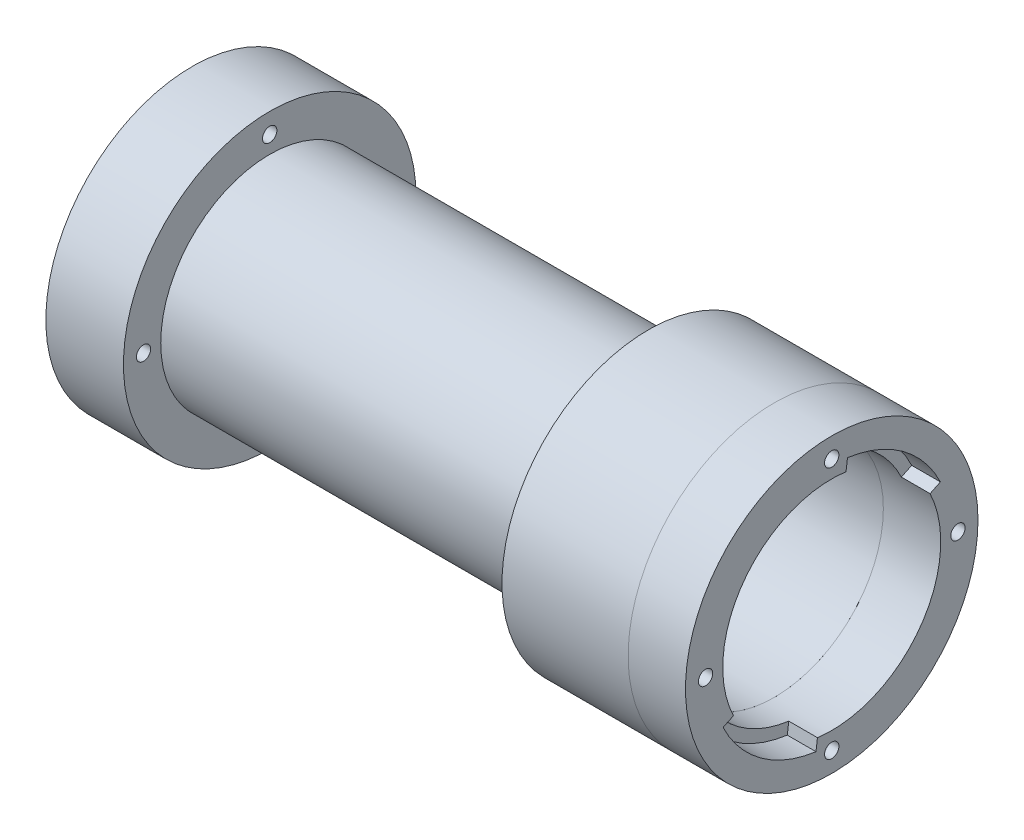
SolidWorks part; units mm, degrees
ref_plane "前视基准面" through (0, 0, 0) normal (0, 0, 1) x (1, 0, 0)
ref_plane "上视基准面" through (0, 0, 0) normal (0, 1, 0) x (1, 0, 0)
ref_plane "右视基准面" through (0, 0, 0) normal (1, 0, 0) x (0, 0, -1)
sketch "草图1" plane through (0, 0, 0) normal (1, 0, 0) x (0, 0, -1)
  circle A0 centre (0, 0) radius 31
  circle A1 centre (0, 0) radius 51
extrude "凸台-拉伸1" add sketch "草图1" along normal blind 18 and the other way blind 9.06
sketch "草图2" plane through (18, 0, 0) normal (1, 0, 0) x (0, 0, -1)
  circle A0 centre (0, 0) radius 27
  circle A1 centre (0, 0) radius 38
extrude "凸台-拉伸2" add sketch "草图2" along normal blind 132
sketch "草图3" plane through (150, 0, 0) normal (1, 0, 0) x (0, 0, -1)
  circle A0 centre (0, 0) radius 38
  circle A1 centre (0, 0) radius 51
extrude "凸台-拉伸3" add sketch "草图3" along normal blind 63.98 separate body
sketch "草图4" plane through (-9.06, 0, 0) normal (-1, 0, 0) x (0, 0, 1)
  line L0 (0, 0) -> (60.5842, 0) construction
  line L1 (60.5842, 0) -> (-61.6406, 0) construction
  line L2 (0, 0) -> (0, 71.2022) construction
  line L3 (0, 71.2022) -> (0, -60.4245) construction
  circle A0 centre (0, 44) radius 2.5
  circle A1 centre (44, 0) radius 2.5
  circle A2 centre (0, -44) radius 2.5
  circle A3 centre (-44, 0) radius 2.5
  point P17 (0, 0)
  dimension "D1" = 4
extrude "切除-拉伸1" cut sketch "草图4" against normal up to surface (223.04 mm away)
sketch "草图5" plane through (213.98, 0, 0) normal (1, 0, 0) x (0, 0, -1)
  line L12 (4.9791, 37.6724) -> (5.5032, 41.6379)
  line L13 (34.278, 16.4018) -> (37.8862, 18.1283)
  line L14 (-4.9791, -37.6724) -> (-5.5032, -41.6379)
  line L15 (-34.278, -16.4018) -> (-37.8862, -18.1283)
  arc A2 (34.278, 16.4018) -> (29.8966, 23.4563) centre (0, 0) ccw
  circle A3 centre (0, 0) radius 38 construction
  arc A5 (-34.278, -16.4018) -> (-29.8966, -23.4563) centre (0, 0) ccw
  arc A6 (16.9401, 34.0152) -> (29.8966, 23.4563) centre (0, 0) cw
  arc A10 (18.7233, 37.5957) -> (33.0436, 25.9253) centre (0, 0) cw
  arc A15 (18.7233, 37.5957) -> (5.5032, 41.6379) centre (0, 0) ccw
  arc A16 (33.0436, 25.9253) -> (37.8862, 18.1283) centre (0, 0) cw
  arc A17 (16.9401, 34.0152) -> (4.9791, 37.6724) centre (0, 0) ccw
  arc A18 (-16.9401, -34.0152) -> (-29.8966, -23.4563) centre (0, 0) cw
  arc A19 (-18.7233, -37.5957) -> (-33.0436, -25.9253) centre (0, 0) cw
  arc A20 (-18.7233, -37.5957) -> (-5.5032, -41.6379) centre (0, 0) ccw
  arc A21 (-33.0436, -25.9253) -> (-37.8862, -18.1283) centre (0, 0) cw
  arc A22 (-16.9401, -34.0152) -> (-4.9791, -37.6724) centre (0, 0) ccw
  point P22 (0, 0)
  point P27 (0, 0)
extrude "切除-拉伸2" cut sketch "草图5" against normal blind 10
sketch "草图6" plane through (150, 0, 0) normal (1, 0, 0) x (0, 0, -1)
  circle A0 centre (0, 0) radius 31
extrude "切除-拉伸3" cut sketch "草图6" against normal blind 14
ref_plane "基准面1" through (193.98, 0, 0) normal (1, 0, 0) x (0, 0, -1)
split "分割1" trim tools "基准面1" bodies to split 111 resulting bodies 113 114
